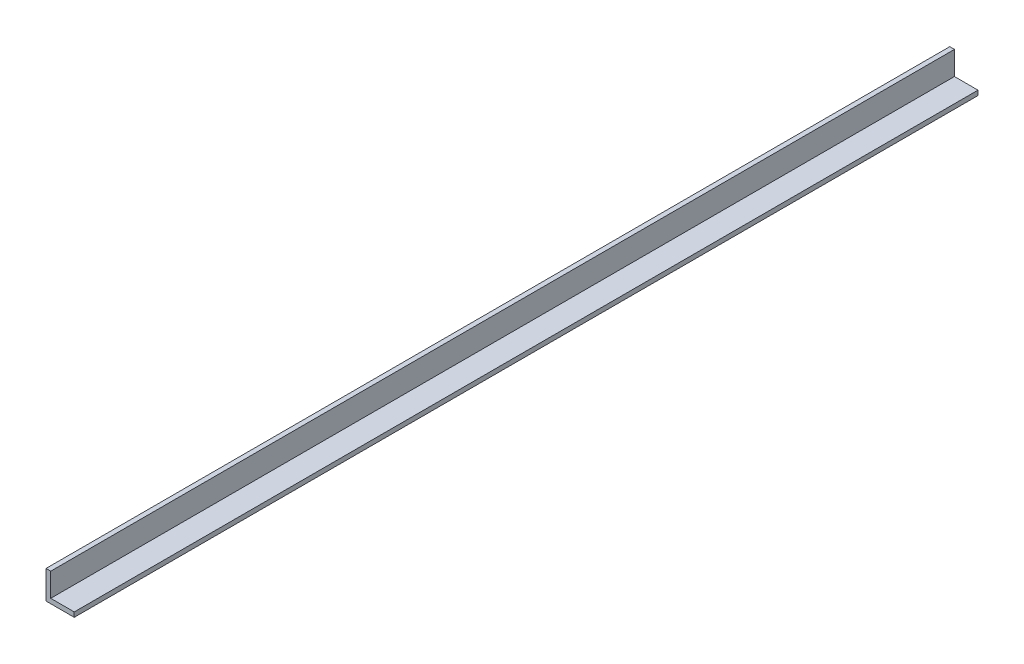
SolidWorks part; units mm, degrees
ref_plane "Front Plane" through (0, 0, 0) normal (0, 0, 1) x (1, 0, 0)
ref_plane "Top Plane" through (0, 0, 0) normal (0, 1, 0) x (1, 0, 0)
ref_plane "Right Plane" through (0, 0, 0) normal (1, 0, 0) x (0, 0, -1)
sketch "Sketch1" plane through (0, 0, 0) normal (0, 0, 1) x (1, 0, 0)
  line L0 (0, 0) -> (19.05, 0)
  line L1 (19.05, 0) -> (19.05, 3.175)
  line L2 (19.05, 3.175) -> (3.175, 3.175)
  line L3 (3.175, 3.175) -> (3.175, 19.05)
  line L4 (3.175, 19.05) -> (0, 19.05)
  line L5 (0, 19.05) -> (0, 0)
  dimension "D1" = 19.05
  dimension "D3" = 3.175
  dimension "D4" = 19.05
extrude "Boss-Extrude1" add sketch "Sketch1" along normal blind 609.6
